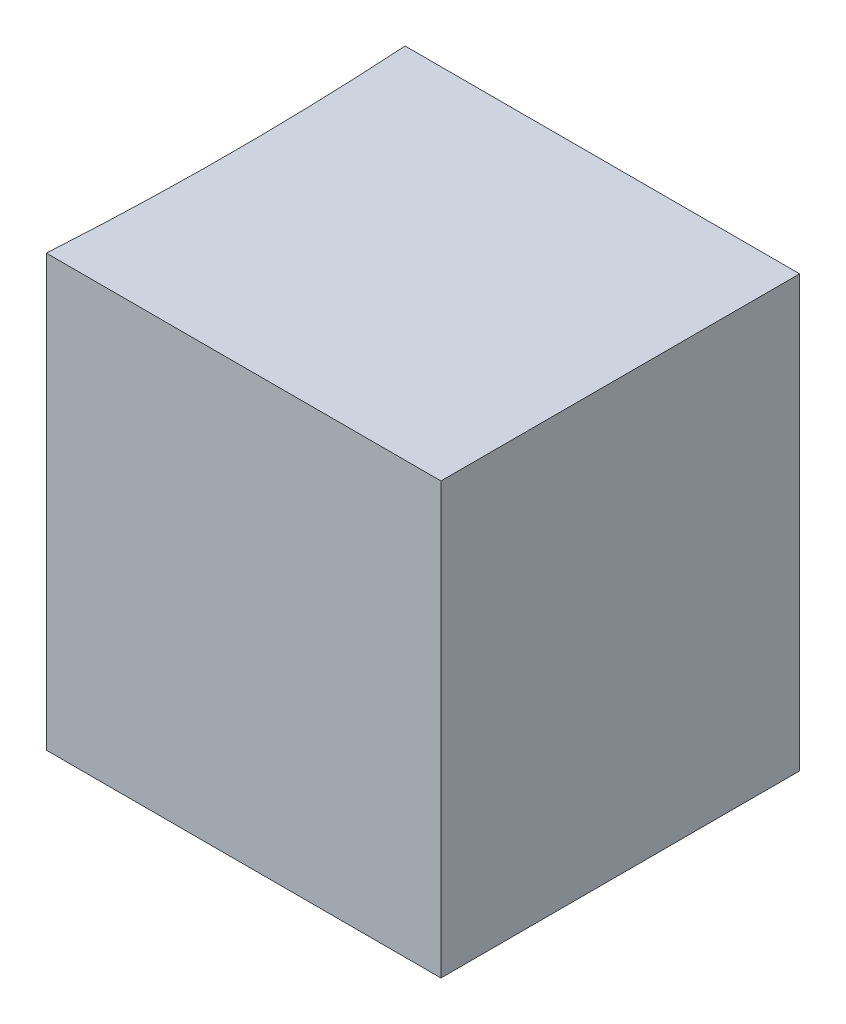
SolidWorks part; units mm, degrees
material "ABS"
ref_plane "Front Plane" through (0, 0, 0) normal (0, 0, 1) x (1, 0, 0)
ref_plane "Top Plane" through (0, 0, 0) normal (0, 1, 0) x (1, 0, 0)
ref_plane "Right Plane" through (0, 0, 0) normal (1, 0, 0) x (0, 0, -1)
other "Bounding Box"
ref_plane "Default Plane" through (115.3714, 0, -6.35) normal (-1, 0, 0) x (0, 0, 1)
sketch "Sketch1" plane through (0, 0, 0) normal (0, 1, 0) x (1, 0, 0)
  line L1 (115.3714, -3.175) -> (115.3714, 6.35)
  line L2 (115.3714, -3.175) -> (115.3714, -6.35)
  line L3 (115.3714, 6.35) -> (101.4014, 6.35)
  line L4 (115.3714, -6.35) -> (101.4014, -6.35)
  arc A5 (101.4014, -6.35) -> (101.4014, 6.35) centre (0, 0) ccw
  dimension "D3" = 12.7
  dimension "D4" = 13.97
  dimension "D5" = 13.97
extrude "Boss-Extrude1" add sketch "Sketch1" along normal blind 15.24
